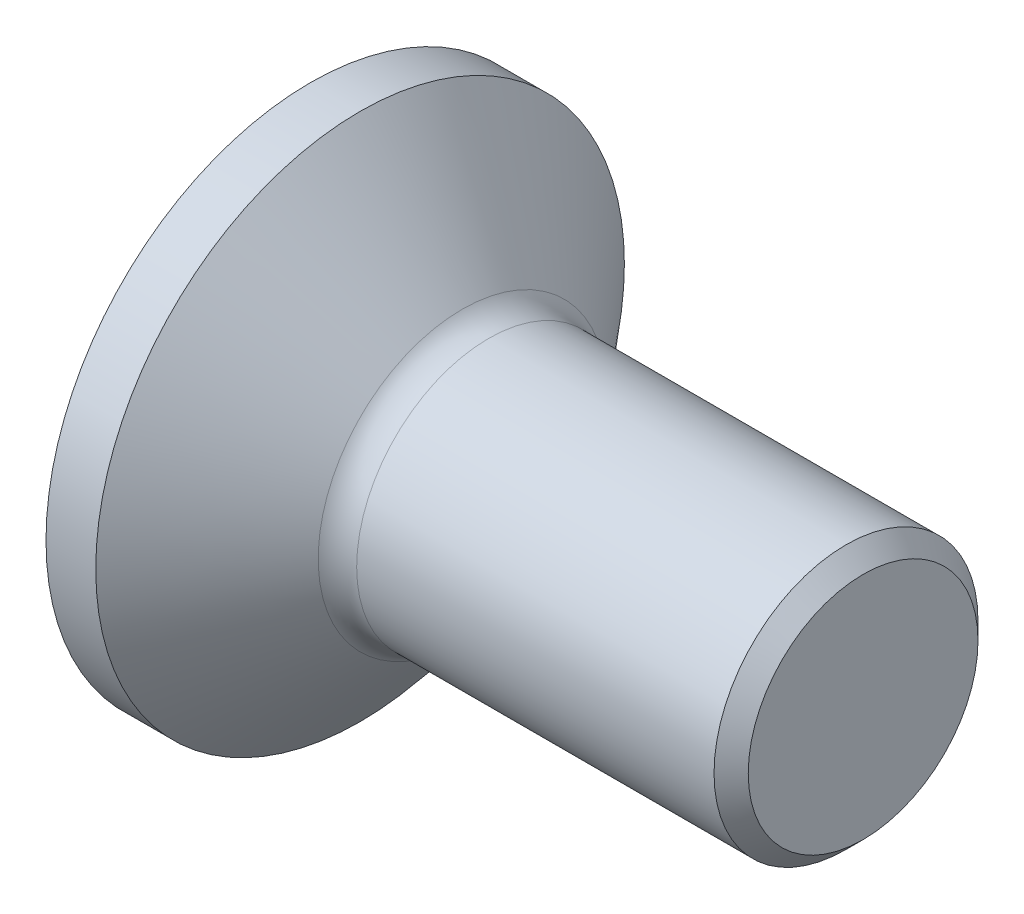
SolidWorks part; units mm, degrees
ref_plane "Front" through (0, 0, 0) normal (0, 0, 1) x (1, 0, 0)
ref_plane "Top" through (0, 0, 0) normal (0, 1, 0) x (1, 0, 0)
ref_plane "Right" through (0, 0, 0) normal (1, 0, 0) x (0, 0, -1)
sketch "Sketch1" plane through (0, 0, 0) normal (0, 0, 1) x (1, 0, 0)
  line L0 (2.5808, 1.91) -> (7.7525, 1.91)
  line L1 (7.7525, 1.91) -> (8, 1.6625)
  line L2 (8, 1.6625) -> (8, 0)
  line L3 (2.2, 2.0859) -> (0.72, 3.825)
  line L4 (0.72, 3.825) -> (0, 3.825)
  line L5 (0, 3.825) -> (0, 0)
  line L6 (0, 0) -> (8, 0)
  line L7 (0, 0) -> (-0.9177, 0) construction
  arc A0 (2.5808, 1.91) -> (2.2, 2.0859) centre (2.5808, 2.41) cw
  dimension "D1" = 8
  dimension "D4" = 0.5
  dimension "D2" = 7.65
  dimension "D3" = 0.72
  dimension "D5" = 3.82
  dimension "D6" = 135
  dimension "D7" = 0.35
  dimension "D8" = 2.2
revolve "Revolve1" add sketch "Sketch1" angle 360 about L7
sketch "Sketch2" plane through (0, 0, 0) normal (-1, 0, 0) x (0, 0, 1)
  line L1 (1.25, 0.7217) -> (0, 1.4434)
  line L2 (0, 1.4434) -> (-1.25, 0.7217)
  line L3 (-1.25, 0.7217) -> (-1.25, -0.7217)
  line L4 (-1.25, -0.7217) -> (0, -1.4434)
  line L5 (0, -1.4434) -> (1.25, -0.7217)
  line L6 (1.25, -0.7217) -> (1.25, 0.7217)
  circle A0 centre (0, 0) radius 1.25 construction
  dimension "D1" = 2.5
extrude "Cut-Extrude1" cut sketch "Sketch2" against normal blind 1.5
